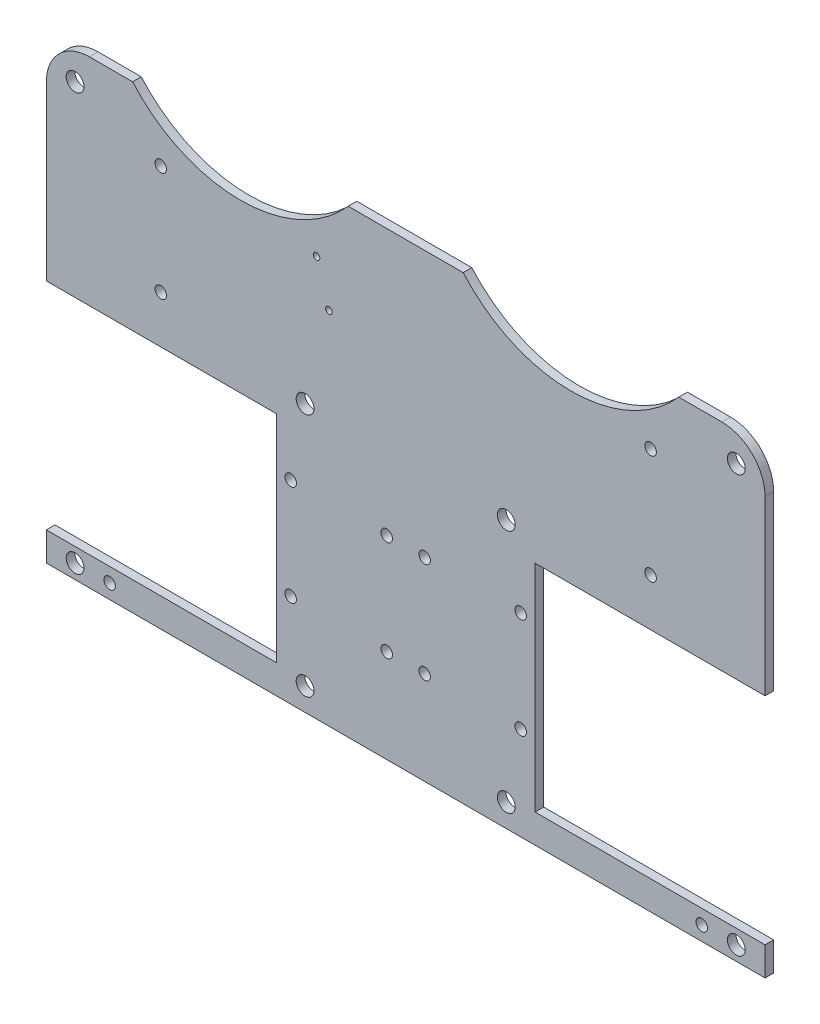
SolidWorks part; units mm, degrees
material "Acier non allié"
ref_plane "Plan de face" through (0, 0, 0) normal (0, 0, 1) x (1, 0, 0)
ref_plane "Plan de dessus" through (0, 0, 0) normal (0, 1, 0) x (1, 0, 0)
ref_plane "Plan de droite" through (0, 0, 0) normal (1, 0, 0) x (0, 0, -1)
sketch "Esquisse1" plane through (0, 0, 0) normal (0, 0, 1) x (1, 0, 0)
  line L1 (0, 0) -> (250, 0)
  line L2 (0, 0) -> (0, -210)
  line L3 (0, -210) -> (250, -210)
  line L4 (250, 0) -> (250, -210)
  circle A0 centre (94.0023, -70.6273) radius 1.143
  circle A1 centre (98.2979, -84.7191) radius 1.1344
  dimension "D1" = 250
  dimension "D2" = 210
extrude "Boss.-Extru.1" add sketch "Esquisse1" along normal blind 3
sketch "Esquisse2" plane through (0, 0, 3) normal (0, 0, 1) x (1, 0, 0)
  line L0 (125, 0) -> (125, -210) construction
  line L1 (250, 0) -> (0, 0) construction
  line L2 (0, -210) -> (250, -210) construction
  line L3 (0, 0) -> (0, -210) construction
  circle A0 centre (18, -137) radius 2.5
  circle A1 centre (18, -188) radius 2.5
  circle A2 centre (85, -142.5) radius 2
  circle A3 centre (118.4, -142.5) radius 2
  circle A4 centre (118.4, -177.5) radius 2
  circle A5 centre (85, -177.5) radius 2
  circle A6 centre (131.6, -177.5) radius 2
  circle A7 centre (165, -177.5) radius 2
  circle A8 centre (165, -142.5) radius 2
  circle A9 centre (131.6, -142.5) radius 2
  circle A10 centre (232, -188) radius 2.5
  circle A11 centre (232, -137) radius 2.5
  dimension "D1" = 5
  dimension "D2" = 5
  dimension "D7" = 4
  dimension "D8" = 4
  dimension "D9" = 4
  dimension "D10" = 4
  dimension "D3" = 51
  dimension "D4" = 18
  dimension "D5" = 22
  dimension "D6" = 18
  dimension "D11" = 85
  dimension "D12" = 85
  dimension "D13" = 33.4
  dimension "D14" = 33.4
  dimension "D15" = 35
  dimension "D16" = 35
  dimension "D17" = 32.5
  dimension "D18" = 32.5
extrude "Enlèv. mat.-Extru.1" cut sketch "Esquisse2" against normal blind 5
sketch "Esquisse3" plane through (0, 0, 3) normal (0, 0, 1) x (1, 0, 0)
  line L0 (125, -50) -> (125, -210) construction
  line L2 (0, -210) -> (250, -210) construction
  line L3 (0, 0) -> (250, 0)
  line L6 (250, 0) -> (250, -50)
  line L7 (250, -210) -> (250, 0) construction
  line L8 (250, -50) -> (0, -50)
  line L9 (0, 0) -> (0, -210) construction
  line L10 (0, -50) -> (0, 0)
  dimension "D1" = 160
  dimension "D2" = 50
extrude "Enlèv. mat.-Extru.2" cut sketch "Esquisse3" against normal blind 5
sketch "Esquisse10" plane through (0, 0, 3) normal (0, 0, 1) x (1, 0, 0)
  line L0 (0, -125) -> (80, -125)
  line L1 (0, -50) -> (0, -210) construction
  line L2 (80, -125) -> (80, -200)
  line L3 (125, -50) -> (125, -210) construction
  line L4 (80, -200) -> (0, -200)
  line L5 (0, -200) -> (0, -125)
  line L6 (0, -210) -> (250, -210) construction
  line L7 (0, -50) -> (250, -50) construction
  line L8 (170, -125) -> (170, -200)
  line L14 (170, -200) -> (250, -200)
  line L15 (250, -200) -> (250, -125)
  line L16 (250, -125) -> (170, -125)
  dimension "D1" = 80
  dimension "D2" = 75
  dimension "D3" = 10
extrude "Enlèv. mat.-Extru.7" cut sketch "Esquisse10" against normal blind 10
sketch "Esquisse12" plane through (0, 0, 3) normal (0, 0, 1) x (1, 0, 0)
  line L0 (80, -125) -> (0, -125) construction
  line L1 (0, -50) -> (0, -125) construction
  line L2 (125, -50) -> (125, -210) construction
  line L6 (0, -50) -> (250, -50) construction
  line L7 (0, -210) -> (250, -210) construction
  circle A0 centre (39.8, -108.5) radius 2
  circle A1 centre (39.8, -70.5) radius 2
  circle A5 centre (210.2, -108.5) radius 2
  circle A6 centre (210.2, -70.5) radius 2
  dimension "D1" = 16.5
  dimension "D5" = 4
  dimension "D6" = 4
  dimension "D2" = 38
  dimension "D3" = 39.8
  dimension "D4" = 39.8
extrude "Enlèv. mat.-Extru.8" cut sketch "Esquisse12" against normal blind 13
sketch "Esquisse18" plane through (0, 0, 3) normal (0, 0, 1) x (1, 0, 0)
  line L0 (0, -200) -> (80, -200) construction
  line L1 (0, -200) -> (0, -210) construction
  line L2 (125, -50) -> (125, -210) construction
  line L4 (0, -50) -> (250, -50) construction
  line L5 (0, -210) -> (250, -210) construction
  circle A0 centre (22, -205) radius 2
  circle A3 centre (228, -205) radius 2
  dimension "D1" = 4
  dimension "D2" = 5
  dimension "D3" = 22
extrude "Enlèv. mat.-Extru.13" cut sketch "Esquisse18" against normal blind 10
sketch "Esquisse19" plane through (0, 0, 3) normal (0, 0, 1) x (1, 0, 0)
  line L0 (0, -210) -> (250, -210) construction
  line L2 (80, -200) -> (80, -125) construction
  line L3 (125, -50) -> (125, -210) construction
  line L4 (0, -50) -> (250, -50) construction
  circle A0 centre (90, -117) radius 3.1
  circle A3 centre (90, -202) radius 3.1
  circle A4 centre (160, -202) radius 3.1
  circle A5 centre (160, -117) radius 3.1
  dimension "D9" = 6.2
  dimension "D12" = 6.2
  dimension "D1" = 8
  dimension "D4" = 10
  dimension "D6" = 10
  dimension "D8" = 85
extrude "Enlèv. mat.-Extru.14" cut sketch "Esquisse19" against normal blind 10
sketch "Esquisse21" plane through (0, 0, 3) normal (0, 0, 1) x (1, 0, 0)
  line L0 (0, -50) -> (250, -50) construction
  line L1 (0, -50) -> (0, -125) construction
  line L2 (0, -200) -> (80, -200) construction
  line L3 (0, -200) -> (0, -210) construction
  line L4 (125, -50) -> (125, -210) construction
  line L5 (0, -210) -> (250, -210) construction
  circle A0 centre (10, -60) radius 3.1
  circle A1 centre (10, -205) radius 3.1
  circle A2 centre (240, -205) radius 3.1
  circle A3 centre (240, -60) radius 3.1
  dimension "D1" = 6.2
  dimension "D2" = 6.2
  dimension "D3" = 10
  dimension "D4" = 10
  dimension "D5" = 5
  dimension "D6" = 10
extrude "Enlèv. mat.-Extru.16" cut sketch "Esquisse21" against normal blind 10
sketch "Esquisse23" plane through (0, 0, 3) normal (0, 0, 1) x (1, 0, 0)
  line L0 (0, -50) -> (0, -125) construction
  line L1 (0, -50) -> (250, -50) construction
  line L2 (0, -50) -> (0, -65)
  line L3 (0, -50) -> (15, -50)
  line L4 (125, -50) -> (125, -210) construction
  line L5 (0, -210) -> (250, -210) construction
  line L6 (250, -50) -> (235, -50)
  line L7 (250, -50) -> (250, -65)
  arc A0 (0, -65) -> (15, -50) centre (15, -65) cw
  arc A1 (250, -65) -> (235, -50) centre (235, -65) ccw
  line M31 (250, -125) -> (250, -50)
  line M32 (250, -50) -> (0, -50)
  line M33 (0, -50) -> (0, -125)
  dimension "D1" = 15
extrude "Enlèv. mat.-Extru.17" cut sketch "Esquisse23" against normal blind 10 contours A0 M33 M32 | A1 M31 M32
sketch "Esquisse24" plane through (0, 0, 3) normal (0, 0, 1) x (1, 0, 0)
  line L0 (15, -50) -> (235, -50) construction
  line L1 (0, -65) -> (0, -125) construction
  line L2 (125, -50) -> (125, -210) construction
  line L3 (0, -210) -> (250, -210) construction
  line L4 (30, -50) -> (105, -50)
  line L5 (145, -50) -> (220, -50)
  arc A0 (30, -50) -> (105, -50) centre (67.5, -16.9281) ccw
  arc A1 (220, -50) -> (145, -50) centre (182.5, -16.9281) cw
  dimension "D2" = 50
  dimension "D1" = 75
  dimension "D3" = 30
extrude "Enlèv. mat.-Extru.18" cut sketch "Esquisse24" against normal blind 10 contours L4 A0 | L5 A1
